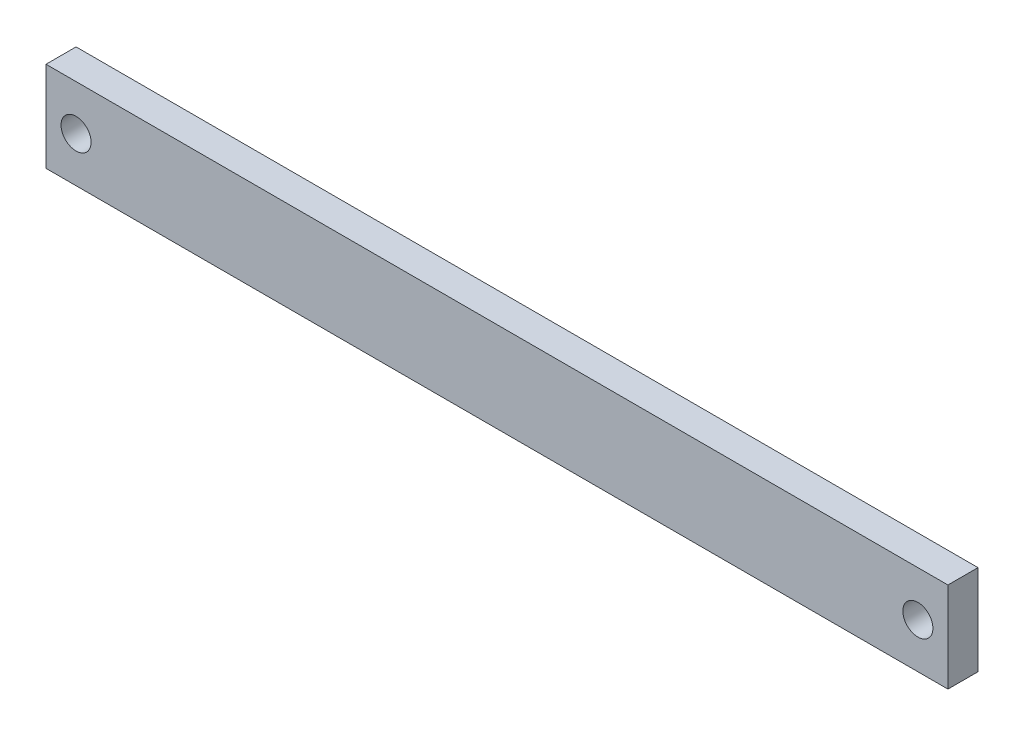
SolidWorks part; units mm, degrees
ref_plane "Front Plane" through (0, 0, 0) normal (0, 0, 1) x (1, 0, 0)
ref_plane "Top Plane" through (0, 0, 0) normal (0, 1, 0) x (1, 0, 0)
ref_plane "Right Plane" through (0, 0, 0) normal (1, 0, 0) x (0, 0, -1)
sketch "Sketch1" plane through (0, 0, 0) normal (0, 0, 1) x (1, 0, 0)
  line L1 (-75, -7.5) -> (75, -7.5)
  line L2 (-75, -7.5) -> (-75, 7.5)
  line L3 (-75, 7.5) -> (75, 7.5)
  line L4 (75, -7.5) -> (75, 7.5)
  line L5 (-75, -7.5) -> (75, 7.5) construction
  line L6 (-75, 7.5) -> (75, -7.5) construction
  circle A0 centre (70, 0) radius 2.5
  circle A1 centre (-70, 0) radius 2.5
  point P0 (0, 0)
  point P10 (0, 0)
  point P11 (-75, 0)
  point P12 (0, 0)
  point P13 (75, 0)
  point P14 (0, 0)
  dimension "D1" = 5
  dimension "D2" = 15
  dimension "D3" = 5
  dimension "D4" = 5
  dimension "D5" = 150
extrude "Boss-Extrude1" add sketch "Sketch1" along normal blind 5
equation "\"D4@Sketch1\"=\"D3@Sketch1\""
